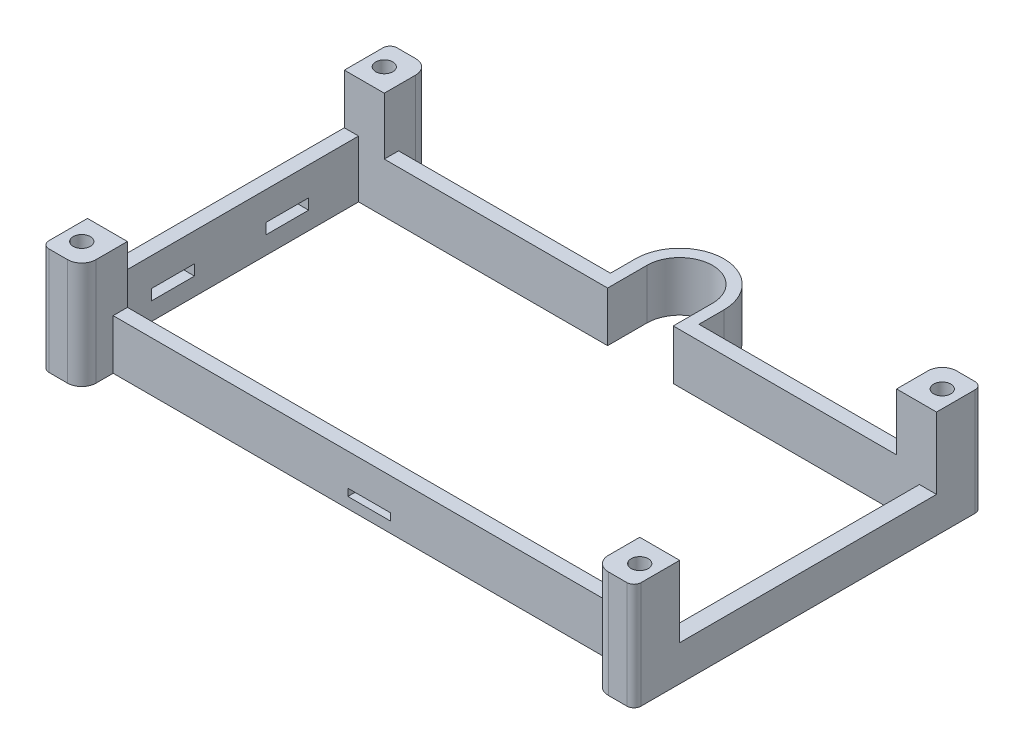
SolidWorks part; units mm, degrees
material "ABS PC"
ref_plane "Front Plane" through (0, 0, 0) normal (0, 0, 1) x (1, 0, 0)
ref_plane "Top Plane" through (0, 0, 0) normal (0, 1, 0) x (1, 0, 0)
ref_plane "Right Plane" through (0, 0, 0) normal (1, 0, 0) x (0, 0, -1)
sketch "Sketch1" plane through (0, 0, 0) normal (0, 1, 0) x (1, 0, 0)
  line L0 (2.4, -23.4) -> (2.4, 23.4)
  line L6 (0, 18) -> (0, -18)
  line L7 (0, -18) -> (-15, -18)
  line L8 (-15, -18) -> (-15, -20)
  line L9 (-15, -20) -> (-3.2, -20)
  line L10 (-3.2, -20) -> (-3.2, -22.4)
  line L11 (-1.2, -24.4) -> (1.4, -24.4)
  line L12 (0, 0) -> (8.7, 0) construction
  line L13 (-1.2, 24.4) -> (1.4, 24.4)
  line L14 (-3.2, 20) -> (-3.2, 22.4)
  line L15 (-15, 20) -> (-3.2, 20)
  line L16 (-15, 18) -> (-15, 20)
  line L17 (0, 18) -> (-15, 18)
  arc A2 (-3.2, -22.4) -> (-1.2, -24.4) centre (-1.2, -22.4) ccw
  arc A3 (1.4, -24.4) -> (2.4, -23.4) centre (1.4, -23.4) ccw
  arc A4 (1.4, 24.4) -> (2.4, 23.4) centre (1.4, 23.4) cw
  arc A5 (-3.2, 22.4) -> (-1.2, 24.4) centre (-1.2, 22.4) cw
  circle A6 centre (0, -21.2) radius 1.2
  circle A7 centre (0, 21.2) radius 1.2
  point P22 (2.4, 0)
  point P29 (0, 0)
  dimension "D7" = 2
  dimension "D8" = 1
  dimension "D14" = 2.4
  dimension "D1" = 24.4
  dimension "D2" = 2.4
  dimension "D3" = 2
  dimension "D4" = 18
  dimension "D5" = 15
  dimension "D6" = 5.6
  dimension "D9" = 1
  dimension "D10" = 2.6
  dimension "D11" = 1
  dimension "D12" = 2
  dimension "D13" = 2
  dimension "D15" = 3.2
  dimension "D16" = 2.4
extrude "Boss-Extrude1" add sketch "Sketch1" along normal blind 15
sketch "Sketch3" plane through (0, 0, 0) normal (0, 1, 0) x (1, 0, 0)
  line L0 (-15, -18) -> (-15, 18)
  line L12 (-1.2, -24.4) -> (1.4, -24.4)
  line L13 (-3.2, -20) -> (-3.2, -22.4)
  line L14 (-15, -20) -> (-3.2, -20)
  line L15 (-15, -18) -> (-15, -20)
  line L16 (0, -18) -> (-15, -18)
  line L17 (0, 18) -> (0, -18)
  line L18 (-15, 18) -> (0, 18)
  line L19 (-15, 20) -> (-15, 18)
  line L20 (-3.2, 20) -> (-15, 20)
  line L21 (-3.2, 22.4) -> (-3.2, 20)
  line L22 (1.4, 24.4) -> (-1.2, 24.4)
  line L23 (2.4, -23.4) -> (2.4, 23.4)
  line L24 (-1.2, -24.4) -> (1.4, -24.4) construction
  line L25 (-3.2, -20) -> (-3.2, -22.4) construction
  line L26 (-15, -20) -> (-3.2, -20) construction
  line L27 (-15, -18) -> (-15, -20) construction
  line L28 (0, -18) -> (-15, -18)
  line L29 (0, 18) -> (0, -18)
  line L30 (-15, 18) -> (0, 18)
  line L31 (-15, 20) -> (-15, 18) construction
  line L32 (-3.2, 20) -> (-15, 20) construction
  line L33 (-3.2, 22.4) -> (-3.2, 20) construction
  line L34 (1.4, 24.4) -> (-1.2, 24.4) construction
  line L35 (2.4, -23.4) -> (2.4, 23.4) construction
  arc A4 (1.4, -24.4) -> (2.4, -23.4) centre (1.4, -23.4) ccw
  arc A5 (-3.2, -22.4) -> (-1.2, -24.4) centre (-1.2, -22.4) ccw
  arc A6 (-1.2, 24.4) -> (-3.2, 22.4) centre (-1.2, 22.4) ccw
  arc A7 (2.4, 23.4) -> (1.4, 24.4) centre (1.4, 23.4) ccw
  arc A8 (1.4, -24.4) -> (2.4, -23.4) centre (1.4, -23.4) ccw construction
  arc A9 (-3.2, -22.4) -> (-1.2, -24.4) centre (-1.2, -22.4) ccw construction
  arc A10 (-1.2, 24.4) -> (-3.2, 22.4) centre (-1.2, 22.4) ccw construction
  arc A11 (2.4, 23.4) -> (1.4, 24.4) centre (1.4, 23.4) ccw construction
  dimension "D1" = 0
extrude "Boss-Extrude3" add sketch "Sketch3" along normal blind 1.5
sketch "Sketch4" plane through (-15, 0, 0) normal (-1, 0, 0) x (0, 0, 1)
  line L0 (-18, 1.5) -> (-18, 0)
  line L8 (-20, 0) -> (20, 0)
  line L9 (20, 0) -> (20, 15)
  line L10 (20, 15) -> (18, 15)
  line L11 (18, 15) -> (18, 1.5)
  line L12 (18, 1.5) -> (-18, 1.5)
  line L13 (-18, 1.5) -> (-18, 15)
  line L14 (-18, 15) -> (-20, 15)
  line L15 (-20, 15) -> (-20, 0)
  line L16 (-20, 0) -> (-18, 0)
  line L21 (-18, 1.5) -> (-18, 15)
  line L22 (-18, 15) -> (-20, 15)
  line L23 (-20, 15) -> (-20, 0)
  dimension "D1" = 0
extrude "Boss-Extrude4" add sketch "Sketch4" along normal blind 19.5
sketch "Sketch6" plane through (0, 15, 0) normal (0, 1, 0) x (1, 0, 0)
  line L0 (-49.4072, 20) -> (-29.2339, 20) construction
  line L1 (-45.3, 20) -> (-45.3, 23.5)
  line L2 (-3.2, 20) -> (-34.5, 20) construction
  line L3 (-43.7, 20) -> (-43.7, 23.5)
  line L4 (-43.7, 23.5) -> (-34.5, 23.5) construction
  line L5 (-34.5, 23.5) -> (-34.5, 20)
  line L6 (-32.9, 23.5) -> (-32.9, 20)
  line L7 (-43.7, 18) -> (-80.6, 18)
  line L8 (-80.6, 18) -> (-80.6, 23.4)
  line L9 (-79.6, 24.4) -> (-77, 24.4)
  line L10 (-75, 22.4) -> (-75, 20)
  line L11 (-75, 20) -> (-45.3, 20)
  line L12 (-43.7, 20) -> (-43.7, 18)
  line L13 (-34.5, 20) -> (-32.9, 20)
  line L14 (0, 0) -> (-50000, 0) construction
  line L15 (-80.6, -18) -> (-15, -18)
  line L16 (-75, -20) -> (-15, -20)
  line L17 (-75, -22.4) -> (-75, -20)
  line L18 (-79.6, -24.4) -> (-77, -24.4)
  line L19 (-80.6, -18) -> (-80.6, -23.4)
  line L20 (0, -18) -> (-15, -18) construction
  line L21 (-15, -18) -> (-15, -20) construction
  line L22 (-15, -18) -> (-15, -20)
  arc A0 (-43.7, 23.5) -> (-34.5, 23.5) centre (-39.1, 23.5) cw
  arc A1 (-80.6, 23.4) -> (-79.6, 24.4) centre (-79.6, 23.4) cw
  arc A2 (-77, 24.4) -> (-75, 22.4) centre (-77, 22.4) cw
  arc A3 (-45.3, 23.5) -> (-32.9, 23.5) centre (-39.1, 23.5) cw
  circle A4 centre (-78.2, 21.2) radius 1.2
  circle A5 centre (-78.2, -21.2) radius 1.2
  arc A6 (-77, -24.4) -> (-75, -22.4) centre (-77, -22.4) ccw
  arc A7 (-80.6, -23.4) -> (-79.6, -24.4) centre (-79.6, -23.4) ccw
  dimension "D5" = 1
  dimension "D6" = 2
  dimension "D7" = 2.4
  dimension "D1" = 9.2
  dimension "D2" = 3.5
  dimension "D4" = 2
  dimension "D8" = 2.4
  dimension "D9" = 3.2
  dimension "D10" = 2.6
  dimension "D11" = 36.9
  dimension "D3" = 1.6
extrude "Boss-Extrude5" add sketch "Sketch6" against normal blind 15
sketch "Sketch7" plane through (0, 0, 0) normal (0, -1, 0) x (1, 0, 0)
  line L0 (-80.6, -18) -> (-43.7, -18) construction
  line L1 (-80.6, 18) -> (-78.6, 18)
  line L2 (-80.6, 18) -> (-80.6, -18)
  line L3 (-80.6, -18) -> (-78.6, -18)
  line L4 (-78.6, 18) -> (-78.6, -18)
  dimension "D1" = 2
extrude "Boss-Extrude6" add sketch "Sketch7" against normal blind 8
sketch "Sketch8" plane through (0, 0, 18) normal (0, 0, -1) x (-1, 0, 0)
  line L0 (75, 0) -> (3.2, 0) construction
  line L1 (42.1, 1.5) -> (36.1, 1.5)
  line L2 (42.1, 1.5) -> (42.1, 2.5)
  line L3 (42.1, 2.5) -> (36.1, 2.5)
  line L4 (36.1, 1.5) -> (36.1, 2.5)
  line L5 (75, 0) -> (3.2, 0) construction
  line L6 (39.1, 0) -> (39.1, 50000) construction
  point P8 (39.1, 0)
  point P9 (39.1, 1.5)
  dimension "D1" = 6
  dimension "D2" = 1
  dimension "D3" = 1.5
extrude "Cut-Extrude1" cut sketch "Sketch8" against normal blind 5
sketch "Sketch9" plane through (-78.6, 0, 0) normal (1, 0, 0) x (0, 0, -1)
  line L0 (0, 0) -> (0, 50000) construction
  line L1 (11, 2.5) -> (5, 2.5)
  line L2 (11, 2.5) -> (11, 4)
  line L3 (11, 4) -> (5, 4)
  line L4 (5, 2.5) -> (5, 4)
  line L9 (18, 0) -> (-18, 0) construction
  line L10 (18, 8) -> (-18, 8) construction
  line L11 (-5, 2.5) -> (-5, 4)
  line L12 (-11, 4) -> (-5, 4)
  line L13 (-11, 2.5) -> (-11, 4)
  line L14 (-11, 2.5) -> (-5, 2.5)
  point P8 (0, 0)
  point P11 (0, 8)
  dimension "D1" = 5
  dimension "D2" = 6
  dimension "D3" = 1.5
  dimension "D4" = 2.5
extrude "Cut-Extrude2" cut sketch "Sketch9" against normal blind 5
sketch "Sketch10" plane through (0, 0, -20) normal (0, 0, -1) x (-1, 0, 0)
  line L0 (75, 0) -> (75, 15) construction
  line L1 (75, 7) -> (3.2, 7)
  line L2 (75, 7) -> (75, 15)
  line L3 (75, 15) -> (3.2, 15)
  line L4 (3.2, 7) -> (3.2, 15)
  dimension "D1" = 8
extrude "Cut-Extrude3" cut sketch "Sketch10" against normal through all and the other way through all
sketch "Sketch11" plane through (2.4, 0, 0) normal (1, 0, 0) x (0, 0, -1)
  line L0 (18, 0) -> (-18, 0) construction
  line L1 (18, 0) -> (-18, 0) construction
  line L2 (18, 5) -> (18, 15)
  line L3 (-23.4, 15) -> (23.4, 15) construction
  line L4 (18, 15) -> (-18, 15)
  line L5 (-18, 15) -> (-18, 5)
  line L6 (-18, 5) -> (18, 5)
  point P8 (0, 0)
  point P9 (16.7368, 5)
  dimension "D1" = 10
extrude "Cut-Extrude4" cut sketch "Sketch11" against normal blind 10
sketch "Sketch12" plane through (0, 0, 0) normal (0, -1, 0) x (1, 0, 0)
  line L0 (0, 18) -> (0, -18) construction
  line L1 (0, 18) -> (0, -18)
  line L2 (0, -18) -> (-15, -18)
  line L3 (-15, -18) -> (-15, 18)
  line L4 (-15, 18) -> (0, 18)
extrude "Cut-Extrude5" cut sketch "Sketch12" against normal blind 10
equation "\"ˇ5\"=10.0979"
